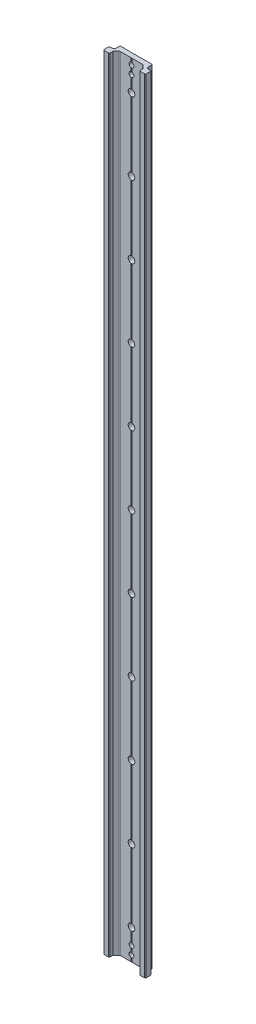
SolidWorks part; units mm, degrees
ref_plane "Plan de face" through (0, 0, 0) normal (0, 0, 1) x (1, 0, 0)
ref_plane "Plan de dessus" through (0, 0, 0) normal (0, 1, 0) x (1, 0, 0)
ref_plane "Plan de droite" through (0, 0, 0) normal (1, 0, 0) x (0, 0, -1)
ref_plane "Plan1" through (0, 325, 0) normal (0, 1, 0) x (1, 0, 0)
sketch "Esquisse1" plane through (0, 325, 0) normal (0, 1, 0) x (1, 0, 0)
  line L0 (-9.7, 1) -> (9.7, 1)
  line L1 (9.7, 1) -> (12.5, -1.8)
  line L2 (12.5, -1.8) -> (12.5, -5)
  line L3 (12.5, -5) -> (17.5, -5)
  line L4 (17.5, -5) -> (17.5, 5)
  line L5 (17.5, 5) -> (-17.5, 5)
  line L6 (-17.5, 5) -> (-17.5, -5)
  line L7 (-17.5, -5) -> (-12.5, -5)
  line L8 (-12.5, -5) -> (-12.5, -1.8)
  line L9 (-12.5, -1.8) -> (-9.7, 1)
extrude "Boss.-Extru.1" add sketch "Esquisse1" against normal blind 650
sketch "Esquisse2" plane through (0, -325, 0) normal (0, -1, 0) x (1, 0, 0)
  line L0 (-14.3, 0) -> (-17.5, 0)
  line L1 (-17.5, 0) -> (-17.5, -5)
  line L2 (-17.5, -5) -> (-13.5, -5)
  line L3 (-13.5, -5) -> (-13.5, -0.8)
  line L4 (-13.5, -0.8) -> (-14.3, 0)
extrude "Enlèv. mat.-Extru.1" cut sketch "Esquisse2" against normal through all
sketch "Esquisse3" plane through (0, -325, 0) normal (0, -1, 0) x (1, 0, 0)
  line L0 (0.25, -1) -> (-0.25, -1)
  line L1 (-0.25, -1) -> (0, -1.1443)
  line L2 (0, -1.1443) -> (0.25, -1)
extrude "Enlèv. mat.-Extru.2" cut sketch "Esquisse3" against normal blind 650
sketch "Esquisse4" plane through (0, -325, 0) normal (0, -1, 0) x (1, 0, 0)
  line L0 (13.5, -0.8) -> (13.5, -5)
  line L1 (13.5, -5) -> (17.5, -5)
  line L2 (17.5, -5) -> (17.5, 0)
  line L3 (17.5, 0) -> (14.3, 0)
  line L4 (14.3, 0) -> (13.5, -0.8)
extrude "Enlèv. mat.-Extru.3" cut sketch "Esquisse4" against normal through all
sketch "Esquisse5" plane through (0, -325, 0) normal (0, -1, 0) x (1, 0, 0)
  line L0 (-7.5, -5) -> (7.5, -5)
  line L1 (7.5, -5) -> (7.4, -4.9)
  line L2 (7.4, -4.9) -> (-7.4, -4.9)
  line L3 (-7.4, -4.9) -> (-7.5, -5)
extrude "Enlèv. mat.-Extru.4" cut sketch "Esquisse5" against normal blind 650
hole_wizard "Diamètre du perçage Ø5.5 (5.5)1" positions "Esquisse7" profile "Esquisse6" hole size "Ø5.5" standard "Ansi Metric"
sketch "Esquisse7" plane through (0, 0, -4.9) normal (0, 0, -1) x (-1, 0, 0)
  point P0 (0, 300)
  point P1 (0, 240)
  point P2 (0, 180)
  point P3 (0, 120)
  point P4 (0, 60)
  point P5 (0, 0)
  point P6 (0, -60)
  point P7 (0, -120)
  point P8 (0, -180)
  point P9 (0, -240)
  point P10 (0, -300)
sketch "Esquisse6" plane through (0, 300, -4.9) normal (1, 0, 0) x (0, 1, 0)
  line L0 (0, 0) -> (0, 9.9)
  line L1 (0, 9.9) -> (2.75, 9.9)
  line L2 (2.75, 9.9) -> (2.75, 0)
  line L5 (2.75, 0) -> (0, 0)
  line L11 (0, -6.35) -> (0, 107.95) construction
  dimension "Diamètre du perçage jusqu'au prochain" = 5.5
  dimension "Profondeur du perçage jusqu'au prochain" = 9.9
chamfer "Chanfrein1" distance 0.5 angle 45 2 edges at (17.5, 0, 5) (-17.5, 0, 5)
chamfer "Chanfrein2" distance 0.3 angle 45 2 edges at (-13.5, 0, -5) (13.5, 0, -5)
chamfer "Chanfrein3" distance 0.5 angle 45 3 edges at (12.5, 0, 5) (-17.5, 0, 0) (-12.5, 0, 5)
chamfer "Chanfrein4" distance 0.5 angle 45 1 edges at (17.5, 0, 0)
fillet "Congé1" radius 1.5 2 edges at (9.7, 0, -1) (-9.7, 0, -1)
fillet "Congé2" radius 2 2 edges at (13.5, 0, -0.8) (-13.5, 0, -0.8)
sketch "Esquisse8" plane through (0, 0, -1) normal (0, 0, 1) x (1, 0, 0)
  line L0 (-9.0787, -325) -> (-0.25, -325) construction
  line L1 (0.25, -325) -> (9.0787, -325) construction
  line L3 (0.25, 325) -> (9.0787, 325) construction
  line L4 (0, 325) -> (0, 302.75) construction
  circle A0 centre (0, -313) radius 2
  circle A3 centre (0, 313) radius 2
  circle A4 centre (0, -320) radius 2
  circle A5 centre (0, 320) radius 2
  dimension "D2" = 4
  dimension "D3" = 4
  dimension "D13" = 4
  dimension "D15" = 4
  dimension "D5" = 12
  dimension "D8" = 12
  dimension "D9" = 0
  dimension "D12" = 0
  dimension "D14" = 5
  dimension "D16" = 5
extrude "Enlèv. mat.-Extru.5" cut sketch "Esquisse8" against normal blind 10
